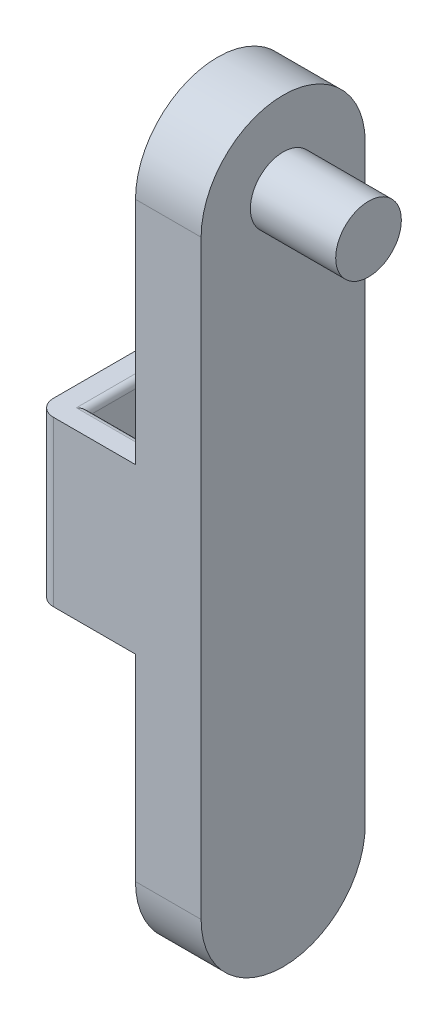
SolidWorks part; units mm, degrees
ref_plane "Front Plane" through (0, 0, 0) normal (0, 0, 1) x (1, 0, 0)
ref_plane "Top Plane" through (0, 0, 0) normal (0, 1, 0) x (1, 0, 0)
ref_plane "Right Plane" through (0, 0, 0) normal (1, 0, 0) x (0, 0, -1)
sketch "Sketch1" plane through (0, 0, 0) normal (1, 0, 0) x (0, 0, -1)
  line L0 (-17.2349, 15.5155) -> (-17.2349, -2.4845)
  line L1 (-12.2349, 15.5155) -> (-12.2349, -2.4845)
  arc A0 (-17.2349, 15.5155) -> (-12.2349, 15.5155) centre (-14.7349, 15.5155) cw
  arc A1 (-12.2349, -2.4845) -> (-17.2349, -2.4845) centre (-14.7349, -2.4845) cw
  dimension "D1" = 18
  dimension "D2" = 5
extrude "Boss-Extrude1" add sketch "Sketch1" along normal blind 2
sketch "Sketch2" plane through (2, 0, 0) normal (1, 0, 0) x (0, 0, -1)
  circle A0 centre (-14.7349, 15.5155) radius 1
  dimension "D1" = 2
extrude "Boss-Extrude2" add sketch "Sketch2" along normal blind 2.6
sketch "Sketch3" plane through (0, 0, 12.2349) normal (0, 0, -1) x (-1, 0, 0)
  line L0 (0, -2.4845) -> (0, 15.5155) construction
  line L1 (0, 8.5155) -> (3, 8.5155)
  line L2 (0, 8.5155) -> (0, 3.5155)
  line L3 (0, 3.5155) -> (3, 3.5155)
  line L4 (3, 8.5155) -> (3, 3.5155)
  line L5 (-2, 15.5155) -> (0, 15.5155) construction
  dimension "D1" = 3
  dimension "D2" = 5
  dimension "D3" = 7
extrude "Boss-Extrude3" add sketch "Sketch3" against normal up to surface (5 mm away) up to face at (1, 6.5155, 17.2349)
sketch "Sketch4" plane through (0, 8.5155, 0) normal (0, 1, 0) x (1, 0, 0)
  line L0 (0, -17.2349) -> (-3, -17.2349) construction
  line L1 (-0.8, -16.4349) -> (-2.2, -16.4349)
  line L2 (-0.8, -16.4349) -> (-0.8, -13.0349)
  line L3 (-0.8, -13.0349) -> (-2.2, -13.0349)
  line L4 (-2.2, -16.4349) -> (-2.2, -13.0349)
  line L5 (-3, -12.2349) -> (0, -12.2349) construction
  line L6 (-3, -17.2349) -> (-3, -12.2349) construction
  line L7 (0, -17.2349) -> (0, -12.2349) construction
  dimension "D1" = 0.8
  dimension "D2" = 0.8
  dimension "D3" = 0.8
  dimension "D4" = 0.8
extrude "Cut-Extrude1" cut sketch "Sketch4" against normal through all
fillet "Fillet1" radius 0.5 2 edges at (-3, 6.0155, 17.2349) (-3, 6.0155, 12.2349)
fillet "Fillet2" radius 0.2 8 edges at (-1.5, 3.5155, 13.0349) (-2.2, 3.5155, 14.7349) (-1.5, 3.5155, 16.4349) (-0.8, 3.5155, 14.7349) (-2.2, 8.5155, 14.7349) (-1.5, 8.5155, 16.4349) (-1.5, 8.5155, 13.0349) (-0.8, 8.5155, 14.7349)
